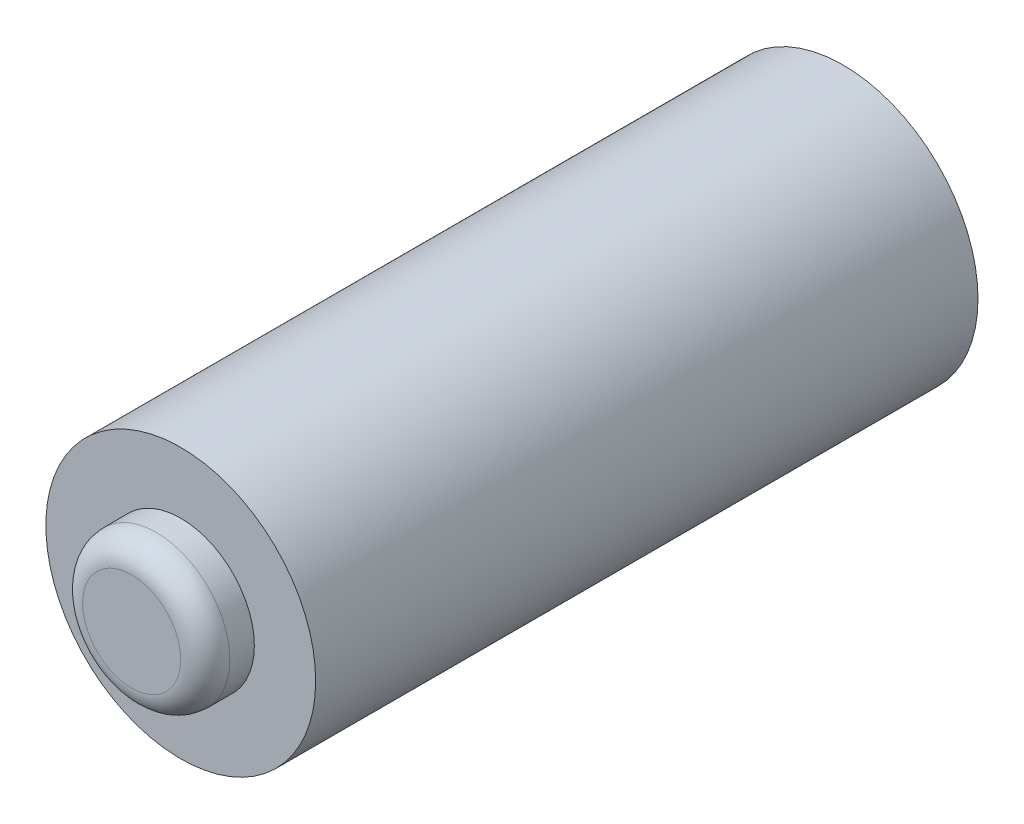
SolidWorks part; units mm, degrees
ref_plane "Front Plane" through (0, 0, 0) normal (0, 0, 1) x (1, 0, 0)
ref_plane "Top Plane" through (0, 0, 0) normal (0, 1, 0) x (1, 0, 0)
ref_plane "Right Plane" through (0, 0, 0) normal (1, 0, 0) x (0, 0, -1)
sketch "Sketch1" plane through (0, 0, 0) normal (0, 0, 1) x (1, 0, 0)
  circle A0 centre (0, 0) radius 2.75
  dimension "D1" = 5.5
extrude "Boss-Extrude1" add sketch "Sketch1" along normal blind 13.5
sketch "Sketch3" plane through (0, 0, 13.5) normal (0, 0, 1) x (1, 0, 0)
  circle A0 centre (0, 0) radius 1.5
  dimension "D1" = 3
extrude "Boss-Extrude2" add sketch "Sketch3" along normal blind 1
fillet "Fillet1" radius 0.5 1 edges at (1.5, 0, 14.5)
sketch "Sketch4" plane through (0, 0, 0) normal (0, 0, -1) x (-1, 0, 0)
  circle A0 centre (0, 0) radius 1.5
  dimension "D1" = 3
extrude "Boss-Extrude3" add sketch "Sketch4" along normal blind 1
fillet "Fillet2" radius 0.5 1 edges at (-1.5, 0, -1)
